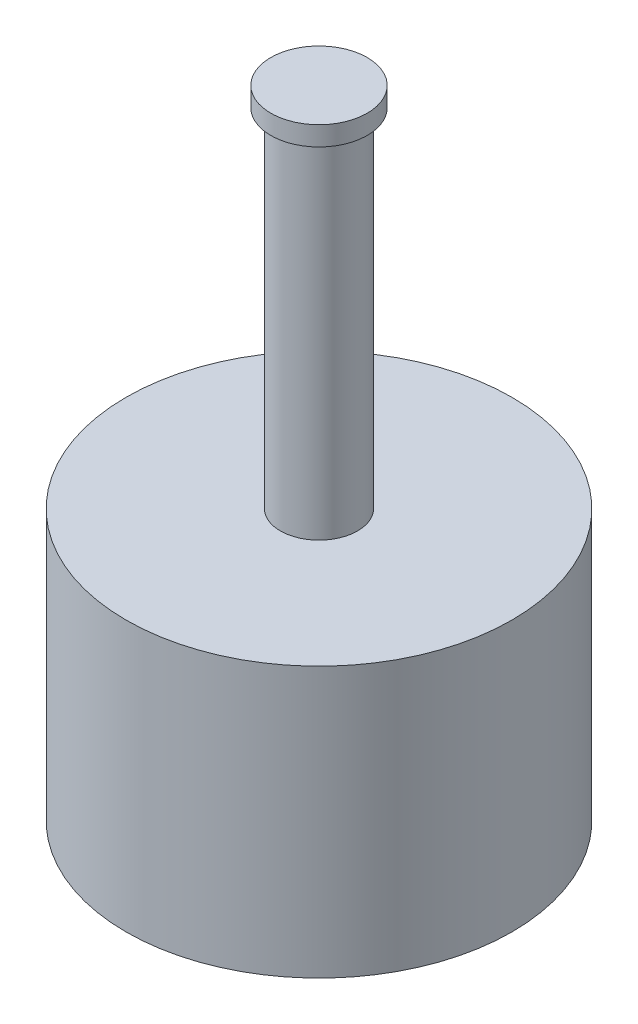
SolidWorks part; units mm, degrees
material "1060 Alloy"
ref_plane "Front Plane" through (0, 0, 0) normal (0, 0, 1) x (1, 0, 0)
ref_plane "Top Plane" through (0, 0, 0) normal (0, 1, 0) x (1, 0, 0)
ref_plane "Right Plane" through (0, 0, 0) normal (1, 0, 0) x (0, 0, -1)
sketch "Sketch1" plane through (0, 0, 0) normal (0, 0, 1) x (1, 0, 0)
  line L0 (0, 0) -> (0, 12) construction
  line L1 (0, 12) -> (2.5, 12)
  line L2 (2.5, 12) -> (2.5, 11)
  line L3 (2.5, 11) -> (2, 11)
  line L4 (2, 11) -> (2, 0)
  line L5 (2, 0) -> (0, 0)
  line L6 (0, 0) -> (0, 12)
  dimension "D1" = 4
  dimension "D2" = 5
  dimension "D3" = 12
  dimension "D4" = 11
revolve "Revolve1" add sketch "Sketch1" angle 360 about L0
sketch "Sketch2" plane through (0, 0, 0) normal (0, -1, 0) x (1, 0, 0)
  circle A1 centre (0, 0) radius 2
  circle A2 centre (0, 0) radius 2
  dimension "D1" = 0
extrude "Boss-Extrude1" add sketch "Sketch2" along normal blind 18 from surface at -11 starting at face at (0, 11, -2.5)
sketch "Sketch3" plane through (0, -7, 0) normal (0, -1, 0) x (1, 0, 0)
  circle A0 centre (0, 0) radius 10
  dimension "D1" = 20
extrude "Boss-Extrude2" add sketch "Sketch3" along normal blind 14
sketch "Sketch4" plane through (0, -21, 0) normal (0, -1, 0) x (1, 0, 0)
  circle A0 centre (0, 0) radius 8.5
  circle A1 centre (0, 0) radius 4
  dimension "D1" = 17
  dimension "D2" = 8
extrude "Cut-Extrude1" cut sketch "Sketch4" against normal blind 0.5
